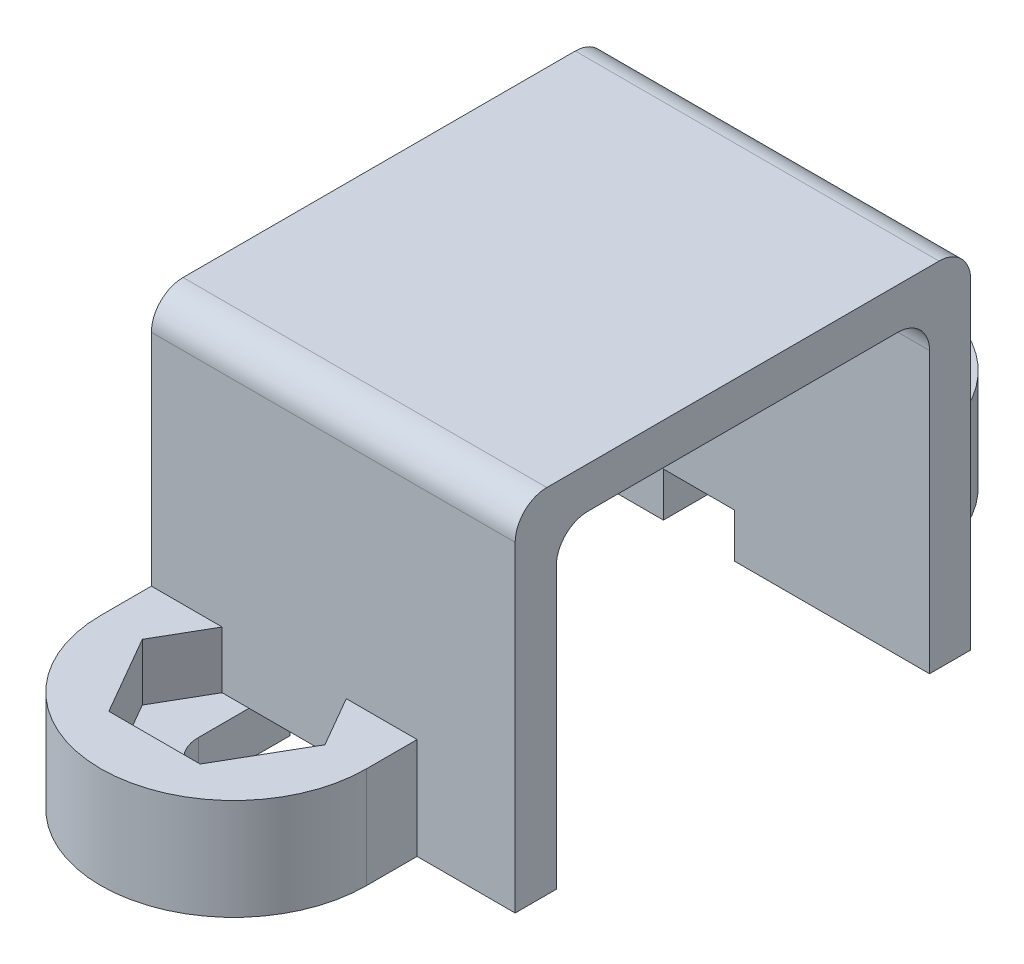
SolidWorks part; units mm, degrees
ref_plane "Front Plane" through (0, 0, 0) normal (0, 0, 1) x (1, 0, 0)
ref_plane "Top Plane" through (0, 0, 0) normal (0, 1, 0) x (1, 0, 0)
ref_plane "Right Plane" through (0, 0, 0) normal (1, 0, 0) x (0, 0, -1)
sketch "草图1" plane through (0, 0, 0) normal (1, 0, 0) x (0, 0, -1)
  line L5 (5.9, 0) -> (5.9, 9.85)
  line L6 (5.9, 9.85) -> (-5.9, 9.85)
  line L11 (-5.9, 9.85) -> (-5.9, 0)
  line L12 (-7.2, 11.15) -> (7.2, 11.15)
  line L13 (-7.2, 11.15) -> (-7.2, 0)
  line L14 (-7.2, 0) -> (-5.9, 0)
  line L15 (5.9, 0) -> (7.2, 0)
  line L16 (7.2, 0) -> (7.2, 11.15)
  point P7 (0, 11.15)
  dimension "D1" = 9.85
  dimension "D2" = 11.8
  dimension "D3" = 14.4
  dimension "D4" = 1.3
extrude "凸台-拉伸1" add sketch "草图1" along normal blind 11.5
fillet "圆角1" radius 1 4 edges at (5.75, 11.15, -7.2) (5.75, 11.15, 7.2) (5.75, 9.85, -5.9) (5.75, 9.85, 5.9)
sketch "草图2" plane through (0, 0, 0) normal (0, 1, 0) x (1, 0, 0)
  line L0 (-1000, 0) -> (49000, 0) construction
  line L1 (0, -1000) -> (0, 49000) construction
  line L2 (0, -7.2) -> (0, -8.8)
  line L3 (8.4, -8.8) -> (8.4, -7.2)
  line L4 (11.5, -7.2) -> (0, -7.2) construction
  line L5 (0, -7.2) -> (8.4, -7.2)
  arc A0 (0, -8.8) -> (8.4, -8.8) centre (4.2, -8.8) ccw
  dimension "D1" = 4.2
  dimension "D2" = 8.8
extrude "凸台-拉伸2" add sketch "草图2" along normal blind 3.2
sketch "草图10" plane through (0, 3.2, 0) normal (0, 1, 0) x (1, 0, 0)
  line L0 (-995.8, -8.8) -> (49004.2, -8.8) construction
  line L1 (4.2, -1008.8) -> (4.2, 48991.2) construction
  line L3 (7.0855, -8.8) -> (6.1617, -7.2)
  line L5 (2.2357, -7.2) -> (1.312, -8.8)
  line L6 (1.312, -8.8) -> (2.7554, -11.3)
  line L7 (2.7554, -11.3) -> (5.6421, -11.3)
  line L8 (5.6421, -11.3) -> (7.0855, -8.8)
  line L10 (2.2357, -7.2) -> (6.1617, -7.2)
  line L13 (4.2, -6.3) -> (4.1987, -6.3) [skipped]
extrude "切除-拉伸1" cut sketch "草图10" against normal blind 1.8
sketch "草图11" plane through (0, 0, 0) normal (0, 1, 0) x (1, 0, 0)
  line L0 (-1000, -8.8) -> (49000, -8.8) construction
  line L1 (4.2, -1008.8) -> (4.2, 48991.2) construction
  line L2 (3.087, -8.8) -> (3.087, -4.9487)
  line L3 (3.087, -4.9487) -> (5.337, -4.9487)
  line L4 (5.337, -4.9487) -> (5.337, -8.8)
  arc A0 (3.087, -8.8) -> (5.337, -8.8) centre (4.212, -8.8) ccw
  dimension "D1" = 2.25
extrude "切除-拉伸2" cut sketch "草图11" along normal blind 1.4
mirror "镜向1" about plane through (0, 0, 0) normal (0, 0, 1) of "切除-拉伸2", "切除-拉伸1", "凸台-拉伸2"
